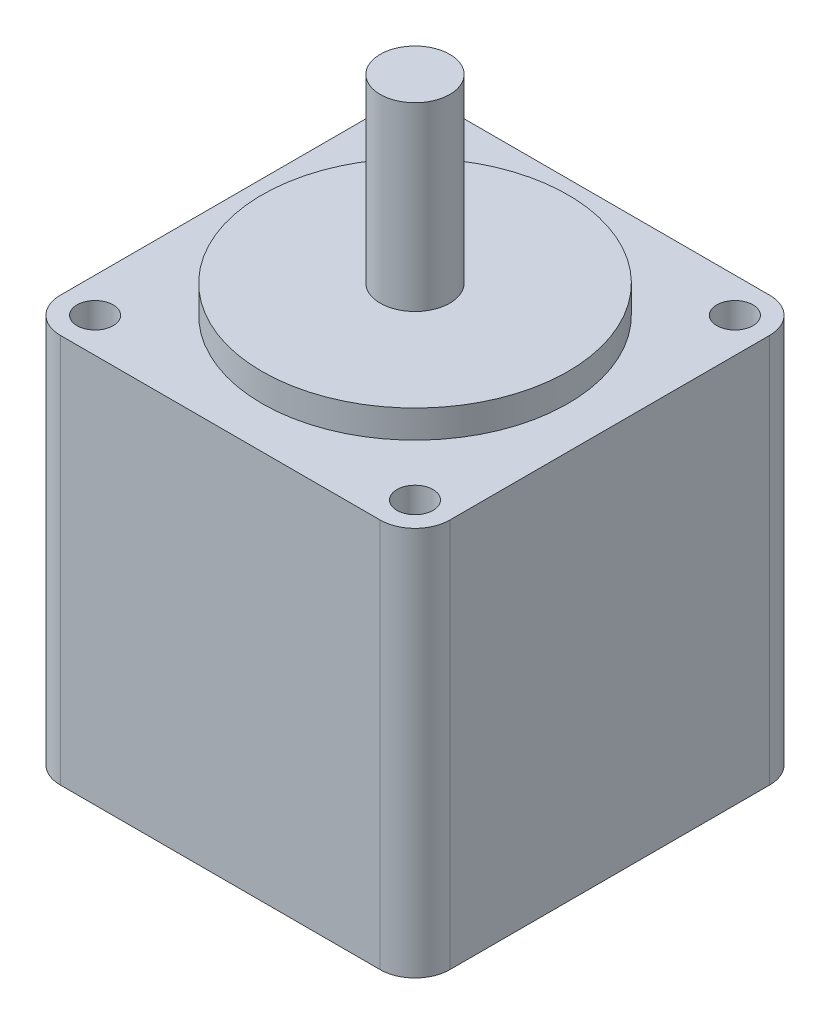
SolidWorks part; units mm, degrees
material "灰铸铁 (SN)"
ref_plane "前视基准面" through (0, 0, 0) normal (0, 0, 1) x (1, 0, 0)
ref_plane "上视基准面" through (0, 0, 0) normal (0, 1, 0) x (1, 0, 0)
ref_plane "右视基准面" through (0, 0, 0) normal (1, 0, 0) x (0, 0, -1)
sketch "草图1" plane through (0, 0, 0) normal (0, 1, 0) x (1, 0, 0)
  line L1 (-11.5, 14) -> (11.5, 14)
  line L2 (-14, 11.5) -> (-14, -11.5)
  line L3 (-11.5, -14) -> (11.5, -14)
  line L4 (14, 11.5) -> (14, -11.5)
  line L5 (-14, 14) -> (14, -14) construction
  line L6 (-14, -14) -> (14, 14) construction
  arc A0 (-14, -11.5) -> (-11.5, -14) centre (-11.5, -11.5) ccw
  arc A1 (11.5, -14) -> (14, -11.5) centre (11.5, -11.5) ccw
  arc A2 (14, 11.5) -> (11.5, 14) centre (11.5, 11.5) ccw
  arc A3 (-14, 11.5) -> (-11.5, 14) centre (-11.5, 11.5) cw
  point P0 (0, 0)
  dimension "D3" = 2.5
  dimension "D1" = 28
  dimension "D2" = 28
extrude "凸台-拉伸1" add sketch "草图1" along normal blind 28
ref_plane "基准面1" through (0, 28, 0) normal (0, 1, 0) x (-1, 0, 0)
sketch "草图2" plane through (0, 28, 0) normal (0, 1, 0) x (-1, 0, 0)
  circle A0 centre (0, 0) radius 11
  dimension "D1" = 22
extrude "凸台-拉伸2" add sketch "草图2" along normal blind 2
ref_plane "基准面2" through (0, 30, 0) normal (0, 1, 0) x (-1, 0, 0)
sketch "草图3" plane through (0, 30, 0) normal (0, 1, 0) x (-1, 0, 0)
  circle A0 centre (0, 0) radius 2.5
  dimension "D1" = 5
extrude "凸台-拉伸3" add sketch "草图3" along normal blind 13
sketch "草图4" plane through (0, 28, 0) normal (0, 1, 0) x (-1, 0, 0)
  line L1 (-11.5, 11.5) -> (11.5, 11.5) construction
  line L2 (-11.5, 11.5) -> (-11.5, -11.5) construction
  line L3 (-11.5, -11.5) -> (11.5, -11.5) construction
  line L4 (11.5, 11.5) -> (11.5, -11.5) construction
  line L5 (-11.5, 11.5) -> (11.5, -11.5) construction
  line L6 (-11.5, -11.5) -> (11.5, 11.5) construction
  circle A0 centre (11.5, 11.5) radius 1.3
  circle A1 centre (11.5, -11.5) radius 1.3
  circle A2 centre (-11.5, -11.5) radius 1.3
  circle A3 centre (-11.5, 11.5) radius 1.3
  point P0 (0, 0)
  dimension "D3" = 2.6
  dimension "D4" = 2.6
  dimension "D5" = 2.6
  dimension "D6" = 2.6
  dimension "D1" = 23
  dimension "D2" = 23
extrude "切除-拉伸1" cut sketch "草图4" against normal blind 5
